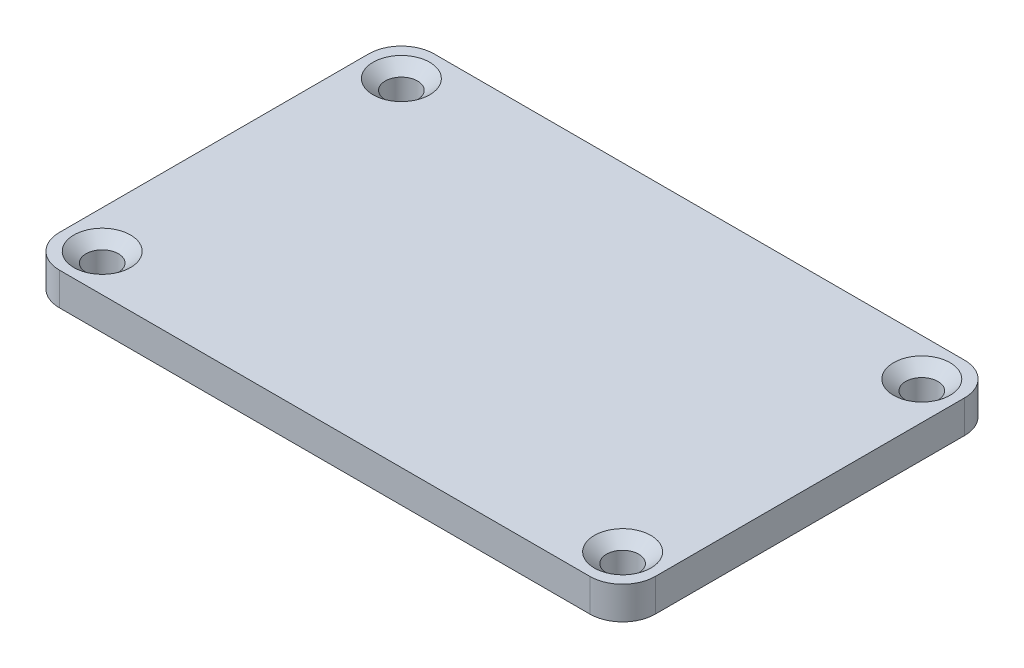
SolidWorks part; units mm, degrees
ref_plane "Front Plane" through (0, 0, 0) normal (0, 0, 1) x (1, 0, 0)
ref_plane "Top Plane" through (0, 0, 0) normal (0, 1, 0) x (1, 0, 0)
ref_plane "Right Plane" through (0, 0, 0) normal (1, 0, 0) x (0, 0, -1)
sketch "Sketch1" plane through (0, 0, 0) normal (0, 1, 0) x (1, 0, 0)
  line L1 (-30.099, -18.923) -> (30.099, -18.923)
  line L2 (-30.099, -18.923) -> (-30.099, 18.923)
  line L3 (-30.099, 18.923) -> (30.099, 18.923)
  line L4 (30.099, -18.923) -> (30.099, 18.923)
  line L5 (-30.099, -18.923) -> (30.099, 18.923) construction
  line L6 (-30.099, 18.923) -> (30.099, -18.923) construction
  point P0 (0, 0)
  dimension "D1" = 60.198
  dimension "D2" = 37.846
extrude "Boss-Extrude1" add sketch "Sketch1" along normal blind 3.302
fillet "Fillet1" radius 3.302 4 edges at (30.099, 1.651, 18.923) (30.099, 1.651, -18.923) (-30.099, 1.651, -18.923) (-30.099, 1.651, 18.923)
hole_wizard "CSK for #4 Flat Head Machine Screw (100)1" positions "Sketch3" profile "Sketch4" countersink size "#4" standard "ANSI Inch" end condition through all
sketch "Sketch3" plane through (0, 3.302, 0) normal (0, 1, 0) x (1, 0, 0)
  line L0 (0, 18.923) -> (0, 0) construction
  line L1 (26.797, 18.923) -> (-26.797, 18.923) construction
  line L2 (0, 0) -> (30.099, 0) construction
  line L3 (30.099, -15.621) -> (30.099, 15.621) construction
  point P0 (-26.289, 15.113)
  point P2 (-26.289, -15.113)
  point P4 (26.289, -15.113)
  point P6 (26.289, 15.113)
  dimension "D1" = 30.226
  dimension "D2" = 52.578
sketch "Sketch4" plane through (-26.289, 3.302, -15.113) normal (1, 0, 0) x (0, 0, 1)
  line L0 (0, 0) -> (0, 3.302)
  line L1 (0, 3.302) -> (1.6319, 3.302)
  line L2 (1.6319, 3.302) -> (1.6319, 1.0284)
  line L3 (1.6319, 1.0284) -> (2.8575, 0)
  line L5 (2.8575, 0) -> (0, 0)
  line L6 (-1.6319, 1.0284) -> (-2.8575, 0) construction
  line L11 (0, -6.35) -> (0, 107.95) construction
  dimension "Thru Hole Dia." = 3.2639
  dimension "Thru Hole Depth" = 3.302
  dimension "Near C'Sink Dia." = 5.715
  dimension "Near C'Sink Angle" = 100
